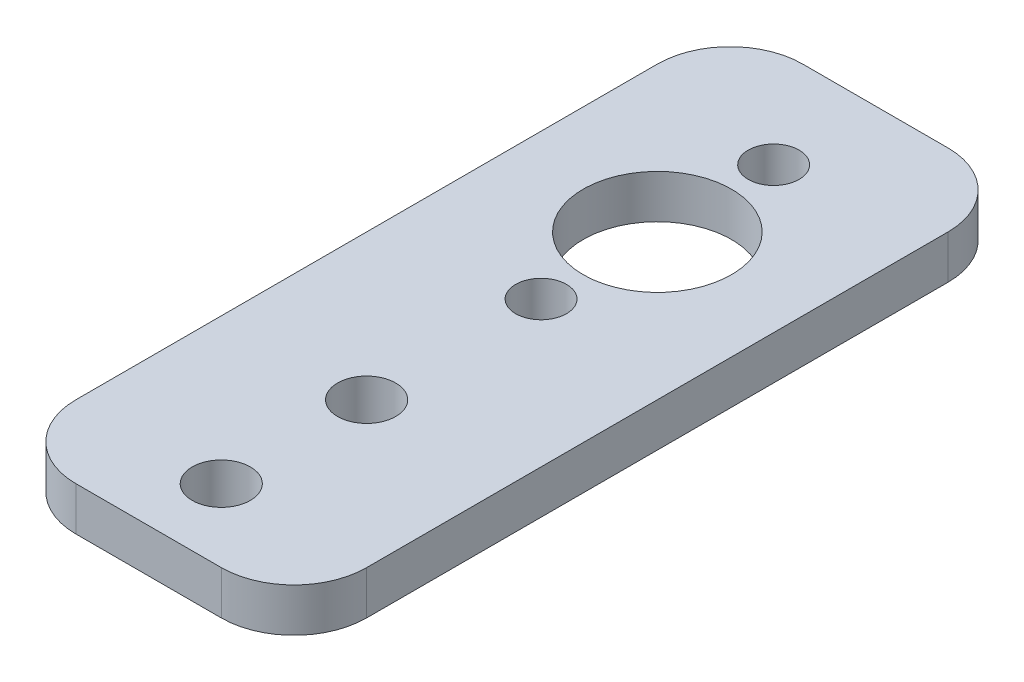
SolidWorks part; units mm, degrees
ref_plane "Front Plane" through (0, 0, 0) normal (0, 0, 1) x (1, 0, 0)
ref_plane "Top Plane" through (0, 0, 0) normal (0, 1, 0) x (1, 0, 0)
ref_plane "Right Plane" through (0, 0, 0) normal (1, 0, 0) x (0, 0, -1)
sketch "Sketch1" plane through (0, 0, 0) normal (0, 1, 0) x (1, 0, 0)
  line L6 (-10, 25) -> (10, 25)
  line L7 (-10, 25) -> (-10, -25)
  line L8 (-10, -25) -> (10, -25)
  line L9 (10, 25) -> (10, -25)
  line L10 (-10, 25) -> (10, -25) construction
  line L11 (-10, -25) -> (10, 25) construction
  point P0 (0, 0)
  dimension "D1" = 20
  dimension "D2" = 50
extrude "Boss-Extrude1" add sketch "Sketch1" along normal blind 3
sketch "Sketch2" plane through (0, 3, 0) normal (0, 1, 0) x (1, 0, 0)
  line L0 (0, -1000) -> (0, 49000) construction
  line L1 (10, 25) -> (-10, 25) construction
  line L3 (-10, -25) -> (10, -25) construction
  circle A2 centre (0, 10) radius 5.1
  circle A3 centre (0, 10) radius 8 construction
  circle A4 centre (0, 18) radius 1.75
  circle A5 centre (8, 10) radius 1.75 construction
  circle A6 centre (0, 2) radius 1.75
  circle A7 centre (-8, 10) radius 1.75 construction
  circle A8 centre (0, -10) radius 2
  circle A9 centre (0, -20) radius 2
  dimension "D2" = 4
  dimension "D5" = 10.2
  dimension "D6" = 16
  dimension "D7" = 3.5
  dimension "D3" = 5
  dimension "D4" = 10
  dimension "D1" = 15
extrude "Cut-Extrude1" cut sketch "Sketch2" against normal through all
fillet "Fillet1" radius 5 4 edges at (10, 1.5, 25) (-10, 1.5, 25) (-10, 1.5, -25) (10, 1.5, -25)
